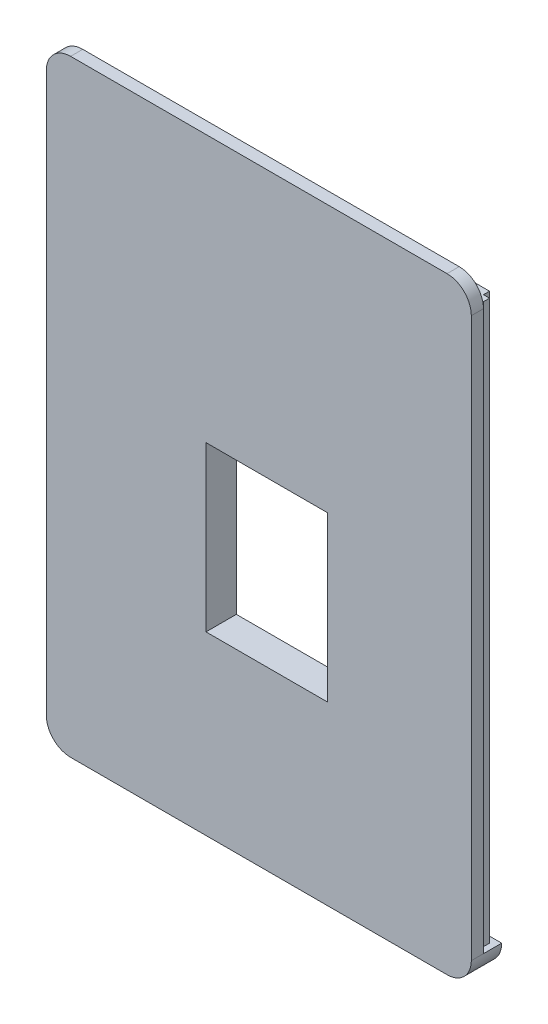
SolidWorks part; units mm, degrees
ref_plane "Front Plane" through (0, 0, 0) normal (1, 0, 0) x (0, 1, 0)
ref_plane "Top Plane" through (0, 0, 0) normal (0, 0, 1) x (0, 1, 0)
ref_plane "Right Plane" through (0, 0, 0) normal (0, 1, 0) x (-1, 0, 0)
sketch "Sketch1" plane through (0, 0, 0) normal (0, 0, 1) x (0, 1, 0)
  line L1 (-50, -35) -> (50, -35)
  line L2 (-50, -35) -> (-50, 35)
  line L3 (-50, 35) -> (50, 35)
  line L4 (50, -35) -> (50, 35)
  line L5 (-50, -35) -> (50, 35) construction
  line L6 (-50, 35) -> (50, -35) construction
  point P0 (0, 0)
  dimension "D1" = 100
  dimension "D2" = 70
extrude "Boss-Extrude1" add sketch "Sketch1" along normal blind 5
sketch "Sketch2" plane through (0, 0, 5) normal (0, 0, 1) x (1, 0, 0)
fillet "Fillet1" radius 4 4 edges at (-35, -50, 2.5) (35, -50, 2.5) (35, 50, 2.5) (-35, 50, 2.5)
sketch "Sketch3" plane through (0, 0, 0) normal (0, 0, -1) x (1, 0, 0)
  line L0 (-35, -46) -> (-35, 46) construction
  line L1 (-8.7, -6.05) -> (11.3, -6.05)
  line L2 (-8.7, -6.05) -> (-8.7, 20.95)
  line L3 (-8.7, 20.95) -> (11.3, 20.95)
  line L4 (11.3, -6.05) -> (11.3, 20.95)
  line L5 (-8.7, -6.05) -> (11.3, 20.95) construction
  line L6 (-8.7, 20.95) -> (11.3, -6.05) construction
  line L7 (31, -50) -> (-31, -50) construction
  point P0 (1.3, 7.45)
  dimension "D1" = 27
  dimension "D2" = 20
  dimension "D3" = 26.3
  dimension "D4" = 43.95
extrude "Cut-Extrude1" cut sketch "Sketch3" against normal blind 5
sketch "Sketch5" plane through (0, 50, 0) normal (0, 1, 0) x (-1, 0, 0)
  line L0 (-35, 0) -> (-35, 5) construction
  line L1 (-35, 3) -> (-33, 3)
  line L2 (-35, 3) -> (-35, 0)
  line L3 (-35, 0) -> (-33, 0)
  line L4 (35, 3) -> (35, 0)
  line L6 (-34, 2) -> (-33, 2)
  line L7 (-34, 2) -> (-34, 1)
  line L8 (-34, 1) -> (-33, 1)
  line L11 (33, 2) -> (34, 2)
  line L13 (33, 1) -> (34, 1)
  line L14 (34, 2) -> (34, 1)
  line L15 (-33, 2) -> (-33, 3)
  line L16 (-33, 1) -> (-33, 0)
  line L17 (33, 2) -> (33, 3)
  line L18 (33, 3) -> (35, 3)
  line L19 (35, 0) -> (33, 0)
  line L20 (33, 0) -> (33, 1)
  line L23 (-31, 5) -> (-31, 0) construction
  dimension "D1" = 64
  dimension "D2" = 65
extrude "Cut-Extrude2" cut sketch "Sketch5" against normal up to vertex (96 mm away)
sketch "Sketch6" plane through (0, 50, 0) normal (0, 1, 0) x (-1, 0, 0)
  line L1 (-35, 3) -> (35, 3)
  line L2 (-35, 3) -> (-35, 0)
  line L3 (-35, 0) -> (35, 0)
  line L4 (35, 3) -> (35, 0)
extrude "Cut-Extrude3" cut sketch "Sketch6" against normal up to vertex (4 mm away) up to point (35, 46, 3)
